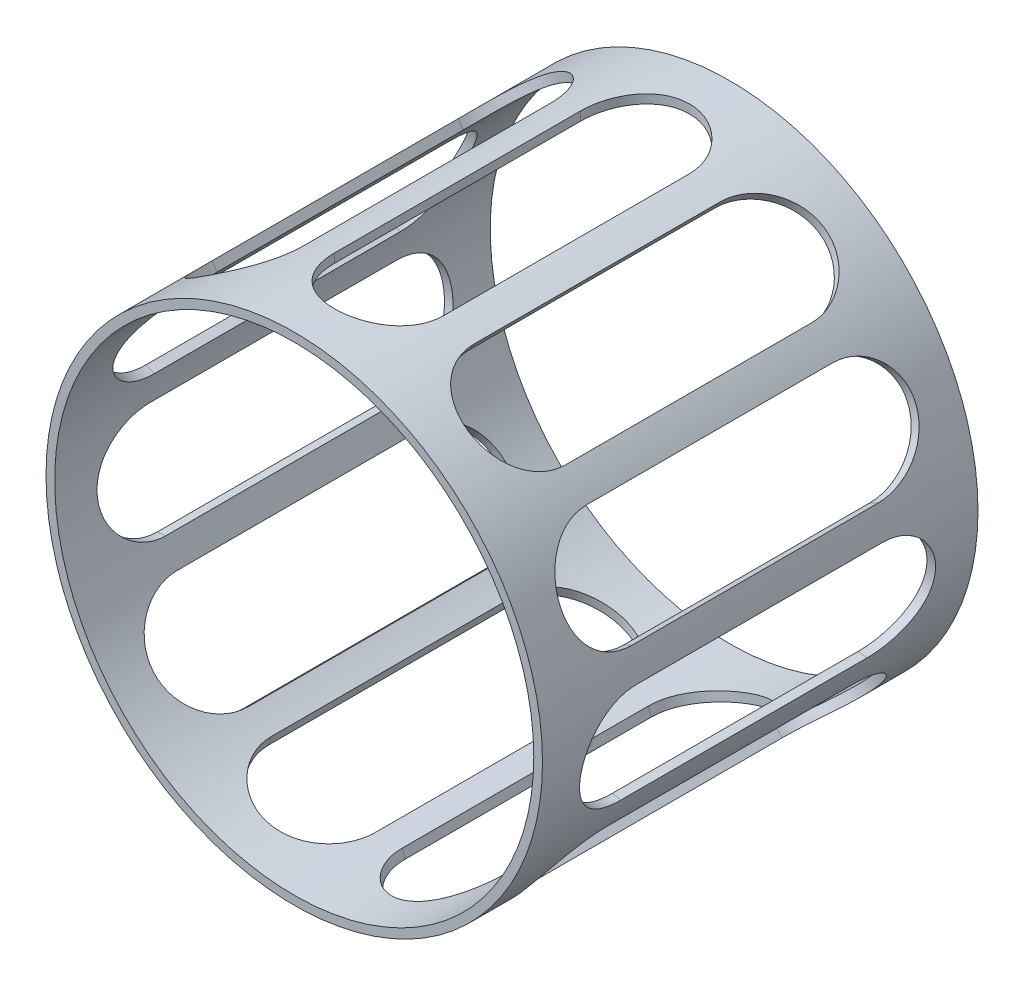
SolidWorks part; units mm, degrees
ref_plane "Front Plane" through (0, 0, 0) normal (0, 0, 1) x (1, 0, 0)
ref_plane "Top Plane" through (0, 0, 0) normal (0, 1, 0) x (1, 0, 0)
ref_plane "Right Plane" through (0, 0, 0) normal (1, 0, 0) x (0, 0, -1)
sketch "Sketch1" plane through (0, 0, 0) normal (0, 0, 1) x (1, 0, 0)
  circle A0 centre (0, 2.3544) radius 110
extrude "Extrude-Thin1" add sketch "Sketch1" along normal blind 200 thin
sketch "Sketch3" plane through (0, 0, 0) normal (0, 1, 0) x (1, 0, 0)
  line L1 (0, -200) -> (0, 0) construction
  line L5 (-25, -43.5) -> (25, -43.5)
  line L6 (-25, -43.5) -> (-25, -156.5)
  line L7 (-25, -156.5) -> (25, -156.5)
  line L8 (25, -43.5) -> (25, -156.5)
  line L9 (-25, -43.5) -> (25, -156.5) construction
  line L10 (-25, -156.5) -> (25, -43.5) construction
  circle A0 centre (0, -43.5) radius 25
  circle A1 centre (0, -156.5) radius 25
  point P0 (0, -100)
extrude "Cut-Extrude1" cut sketch "Sketch3" along normal up to surface (113.5794 mm away) contours L6 L7 L8 L5 | A1 | A0
pattern_circular "CirPattern1" count 11 over 360 about axis through (0, 2.3544, 0) along (0, 0, 1) of "Cut-Extrude1"
